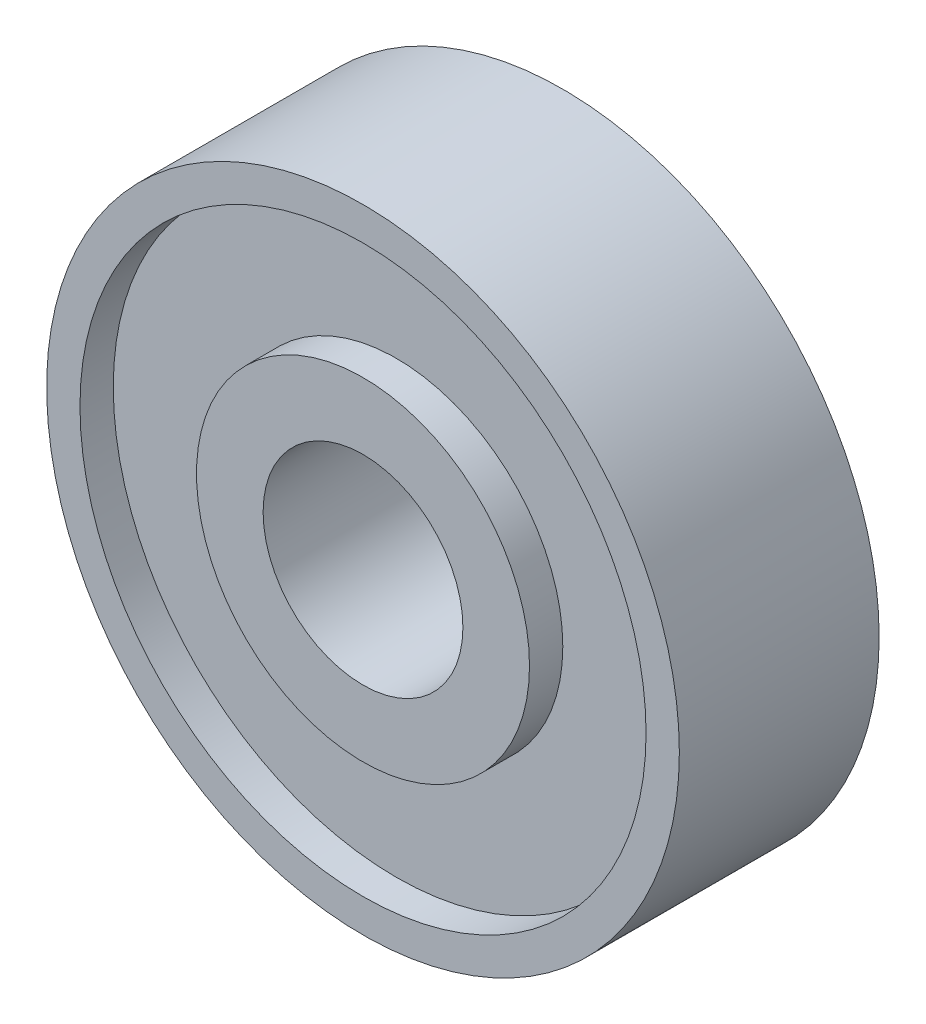
SolidWorks part; units mm, degrees
ref_plane "정면" through (0, 0, 0) normal (0, 0, 1) x (1, 0, 0)
ref_plane "윗면" through (0, 0, 0) normal (0, 1, 0) x (1, 0, 0)
ref_plane "우측면" through (0, 0, 0) normal (1, 0, 0) x (0, 0, -1)
sketch "스케치1" plane through (0, 0, 0) normal (0, 0, 1) x (1, 0, 0)
  circle A0 centre (0, 0) radius 9.5
extrude "돌출1" add sketch "스케치1" along normal blind 6
sketch "스케치2" plane through (0, 0, 6) normal (0, 0, 1) x (1, 0, 0)
  circle A0 centre (0, 0) radius 8.5
extrude "컷-돌출1" cut sketch "스케치2" against normal blind 1
sketch "스케치3" plane through (0, 0, 0) normal (0, 0, -1) x (-1, 0, 0)
  circle A0 centre (0, 0) radius 8.5
extrude "컷-돌출2" cut sketch "스케치3" against normal blind 1
sketch "스케치4" plane through (0, 0, 5) normal (0, 0, 1) x (1, 0, 0)
  circle A0 centre (0, 0) radius 5
extrude "돌출4" add sketch "스케치4" along normal blind 1
sketch "스케치6" plane through (0, 0, 1) normal (0, 0, -1) x (-1, 0, 0)
  circle A0 centre (0, 0) radius 5
extrude "돌출5" add sketch "스케치6" along normal blind 1
sketch "스케치7" plane through (0, 0, 6) normal (0, 0, 1) x (1, 0, 0)
  circle A0 centre (0, 0) radius 3
extrude "컷-돌출3" cut sketch "스케치7" against normal blind 6
